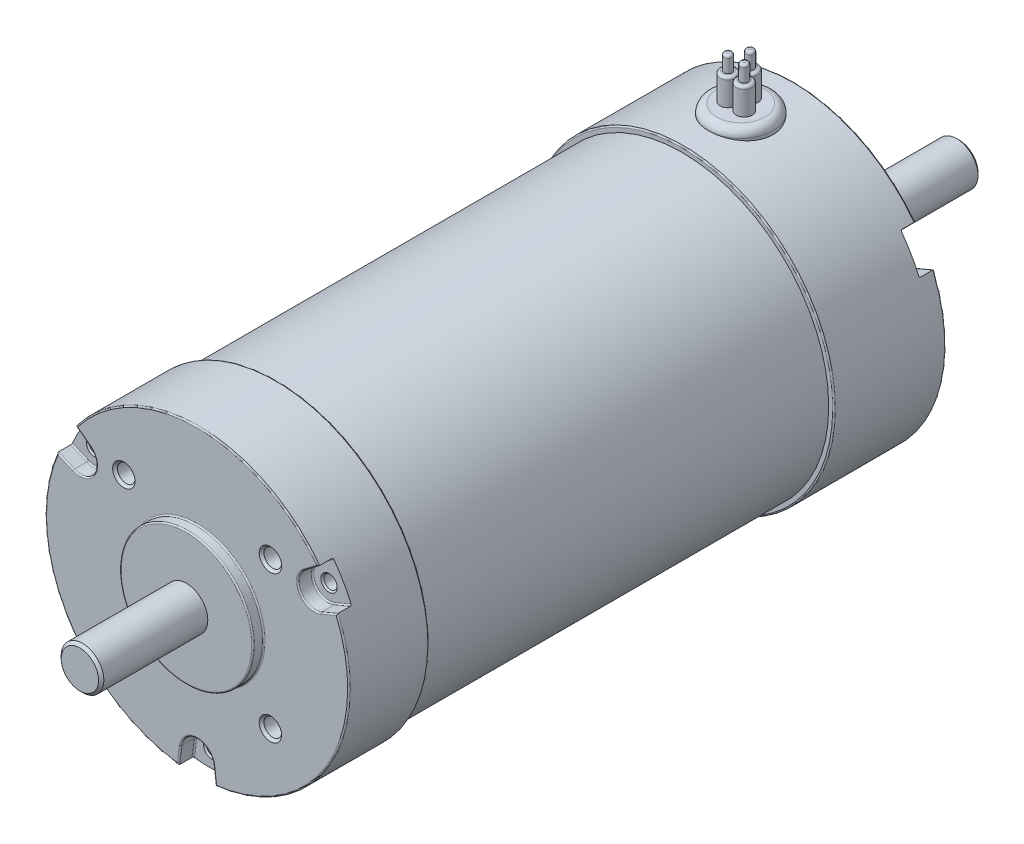
SolidWorks part; units mm, degrees
material "Density BLDC 500W"
ref_plane "Front Plane" through (0, 0, 0) normal (0, 0, 1) x (1, 0, 0)
ref_plane "Top Plane" through (0, 0, 0) normal (0, 1, 0) x (1, 0, 0)
ref_plane "Right Plane" through (0, 0, 0) normal (1, 0, 0) x (0, 0, -1)
sketch "Motor Body Sketch" plane through (0, 0, 0) normal (0, 0, 1) x (1, 0, 0)
  circle A0 centre (0, 0) radius 28.5
  dimension "D1" = 57
extrude "Motor Body" add sketch "Motor Body Sketch" along normal mid plane 112
sketch "Motor Body Cut Out Sketch" plane through (0, 0, 0) normal (0, 0, 1) x (1, 0, 0)
  circle A0 centre (0, 0) radius 27.5
  dimension "D1" = 55
extrude "Motor Body Cut Out" cut sketch "Motor Body Cut Out Sketch" against normal mid plane 76 from offset 3 flip side to cut
sketch "Flange Sketch" plane through (0, 0, 56) normal (0, 0, 1) x (1, 0, 0)
  circle A0 centre (0, 0) radius 12.5
  dimension "D1" = 25
extrude "Flange" add sketch "Flange Sketch" along normal blind 2
sketch "Shaft Sketch" plane through (0, 0, 0) normal (0, 0, 1) x (1, 0, 0)
  circle A0 centre (0, 0) radius 4
  dimension "D1" = 8
extrude "Shaft" add sketch "Shaft Sketch" along normal mid plane 165 from offset 4.5 offset against normal yes
sketch "Fixing Bolts Head Cut Out Sketch" plane through (0, 0, 56) normal (0, 0, 1) x (1, 0, 0)
  line L0 (22.758, 17.1558) -> (20.131, 15.1754)
  line L1 (26.2364, 11.1311) -> (23.2078, 9.8462)
  line L2 (20.131, 15.1754) -> (0, 0) construction
  line L3 (23.2078, 9.8462) -> (0, 0) construction
  line L4 (-3.4783, -28.2869) -> (-3.0768, -25.0217)
  line L5 (3.4783, -28.2869) -> (3.0768, -25.0217)
  line L6 (-22.758, 17.1558) -> (-20.131, 15.1754)
  line L7 (-26.2364, 11.1311) -> (-23.2078, 9.8462)
  line L8 (0, 0) -> (21.997, 12.7) construction
  line L9 (0, 0) -> (0, 16.594) construction
  arc A0 (20.131, 15.1754) -> (23.2078, 9.8462) centre (21.997, 12.7) ccw
  circle A1 centre (0, 0) radius 28.5 construction
  arc A3 (3.0768, -25.0217) -> (-3.0768, -25.0217) centre (0, -25.4) ccw
  circle A4 centre (0, 0) radius 28.5
  arc A5 (26.2364, 11.1311) -> (22.758, 17.1558) centre (0, 0) ccw
  arc A6 (-3.4783, -28.2869) -> (3.4783, -28.2869) centre (0, 0) ccw
  arc A7 (-23.2078, 9.8462) -> (-20.131, 15.1754) centre (-21.997, 12.7) ccw
  arc A8 (-22.758, 17.1558) -> (-26.2364, 11.1311) centre (0, 0) ccw
  point P22 (0, 0)
  dimension "D1" = 25.4
  dimension "D4" = 3.1
  dimension "D2" = 0
  dimension "D5" = 60
  dimension "D3" = 3
extrude "Fixing Bolts Head Cut Out F" cut sketch "Fixing Bolts Head Cut Out Sketch" against normal blind 2.75
hole_wizard "Fixing Holes" positions "Sketch7" profile "Sketch8" tap size "M3" standard "ISO"
sketch "Sketch7" plane through (0, 0, 53.25) normal (0, 0, 1) x (1, 0, 0)
  point P0 (21.997, 12.7)
  point P3 (-21.997, 12.7)
  point P6 (0, -25.4)
sketch "Sketch8" plane through (21.997, 12.7, 53.25) normal (1, 0, 0) x (0, -1, 0)
  line L0 (0, 0) -> (0, 9.2511)
  line L1 (0, 9.2511) -> (1.25, 8.5)
  line L2 (1.25, 8.5) -> (1.25, 0.275)
  line L3 (1.25, 0.275) -> (1.525, 0)
  line L5 (1.525, 0) -> (0, 0)
  line L6 (-1.25, 0.275) -> (-1.525, 0) construction
  line L10 (0, 9.2511) -> (-1.25, 8.5) construction
  line L11 (0, -6.35) -> (0, 107.95) construction
  dimension "Tap Drill Dia." = 2.5
  dimension "Tap Drill Depth" = 8.5
  dimension "Near C'Sink Dia." = 3.05
  dimension "Near C'Sink Angle" = 90
  dimension "Drill Angle" = 118
cosmetic thread "Hole Thread1" parameters "D1"=6, "D2"=3
cosmetic thread "Hole Thread2" parameters "D1"=6, "D2"=3
cosmetic thread "Hole Thread3" parameters "D1"=6, "D2"=3
mirror "Fixing Bolts Back" about plane through (0, 0, 0) normal (0, 0, 1) of "Fixing Holes", "Fixing Bolts Head Cut Out F"
hole_wizard "Front Fixing Holes" positions "Sketch9" profile "Sketch10" tap size "M4" standard "ISO"
sketch "Sketch9" plane through (0, 0, 56) normal (0, 0, 1) x (1, 0, 0)
  line L8 (0, 0) -> (-21.997, 12.7) construction
  line L10 (-13.75, -13.75) -> (13.75, -13.75) construction
  line L11 (13.75, -13.75) -> (-13.75, 13.75) construction
  line L12 (-13.75, 13.75) -> (13.75, 13.75) construction
  line L13 (-13.75, -13.75) -> (-13.75, 13.75) construction
  point P0 (13.75, -13.75)
  point P2 (-13.75, -13.75)
  point P4 (-13.75, 13.75)
  point P6 (13.75, 13.75)
  point P54 (0, 0)
  dimension "D1" = 27.5
  dimension "D2" = 15
sketch "Sketch10" plane through (13.75, -13.75, 56) normal (1, 0, 0) x (0, -1, 0)
  line L0 (0, 0) -> (0, 12.4914)
  line L1 (0, 12.4914) -> (1.65, 11.5)
  line L2 (1.65, 11.5) -> (1.65, 0.45)
  line L3 (1.65, 0.45) -> (2.1, 0)
  line L5 (2.1, 0) -> (0, 0)
  line L6 (-1.65, 0.45) -> (-2.1, 0) construction
  line L10 (0, 12.4914) -> (-1.65, 11.5) construction
  line L11 (0, -6.35) -> (0, 107.95) construction
  dimension "Tap Drill Dia." = 3.3
  dimension "Tap Drill Depth" = 11.5
  dimension "Near C'Sink Dia." = 4.2
  dimension "Near C'Sink Angle" = 90
  dimension "Drill Angle" = 118
cosmetic thread "Hole Thread4" parameters "D1"=8, "D2"=4
cosmetic thread "Hole Thread5" parameters "D1"=8, "D2"=4
cosmetic thread "Hole Thread6" parameters "D1"=8, "D2"=4
cosmetic thread "Hole Thread7" parameters "D1"=8, "D2"=4
chamfer "Aesthetic Chamfer" distance 0.5 angle 45 2 edges at (4, 0, -87) (4, 0, 78)
fillet "Production Fillet" radius 0.25 46 edges at (-24.7221, 10.4887, -53.25) (-21.4445, 16.1656, -53.25) (-24.7221, 10.4887, -56) (-21.4445, 16.1656, -56) (3.2776, -26.6543, -53.25) (-3.2776, -26.6543, -53.25) (3.2776, -26.6543, -56) (-3.2776, -26.6543, -56) (21.4445, 16.1656, -53.25) (24.7221, 10.4887, -53.25) (21.4445, 16.1656, -56) (24.7221, 10.4887, -56) (-24.7221, 10.4887, 53.25) (-21.4445, 16.1656, 53.25) (-24.7221, 10.4887, 56) (-21.4445, 16.1656, 56) (3.2776, -26.6543, 53.25) (-3.2776, -26.6543, 53.25) (3.2776, -26.6543, 56) (-3.2776, -26.6543, 56) (21.4445, 16.1656, 53.25) (24.7221, 10.4887, 53.25) (21.4445, 16.1656, 56) (24.7221, 10.4887, 56) (-19.3124, 11.15, -53.25) (-19.3124, 11.15, -56) (0, -22.3, -53.25) (0, -22.3, -56) (19.3124, 11.15, -53.25) (19.3124, 11.15, -56) (12.5, 0, 56) (12.5, 0, 58) (-19.3124, 11.15, 53.25) (-19.3124, 11.15, 56) (0, -22.3, 53.25) (0, -22.3, 56) (19.3124, 11.15, 53.25) (19.3124, 11.15, 56) (24.6817, -14.25, -56) (-24.6817, -14.25, -56) (0, 28.5, -56) (28.5, 0, -35) (28.5, 0, 41) (-24.6817, -14.25, 56) (0, 28.5, 56) (24.6817, -14.25, 56)
sketch "Wires Rubber Sketch" plane through (0, 0, 0) normal (0, 1, 0) x (1, 0, 0)
  line L0 (22.407, 56) -> (-22.407, 56) construction
  circle A0 centre (0, 46) radius 6
  dimension "D1" = 12
  dimension "D2" = 10
extrude "Wires Rubber" add sketch "Wires Rubber Sketch" along normal blind 30
fillet "Rubber Fillet" radius 1.5 1 edges at (0, 30, -40)
sketch "Wires Insulation Sketch" plane through (0, 30, 0) normal (0, 1, 0) x (1, 0, 0)
  circle A0 centre (0, 46) radius 1.75 construction
  circle A1 centre (0, 47.75) radius 1.5
  point P12 (0, 46)
  dimension "D1" = 3.5
  dimension "D2" = 3
extrude "Wires Insulation" add sketch "Wires Insulation Sketch" along normal blind 5
sketch "Wires Wires Sketch" plane through (0, 35, 0) normal (0, 1, 0) x (1, 0, 0)
  circle A0 centre (0, 47.75) radius 0.75
  dimension "D1" = 1.5
extrude "Wires Wires" add sketch "Wires Wires Sketch" along normal blind 3 contours A0
fillet "Wires Fillet" radius 0.5 2 edges at (0, 38, -47) (0, 35, -46.25)
pattern_circular "Wires" count 3 over 360 about axis through (0, 0, -46) along (0, 1, 0) of "Wires Insulation", "Wires Wires", "Wires Fillet"
